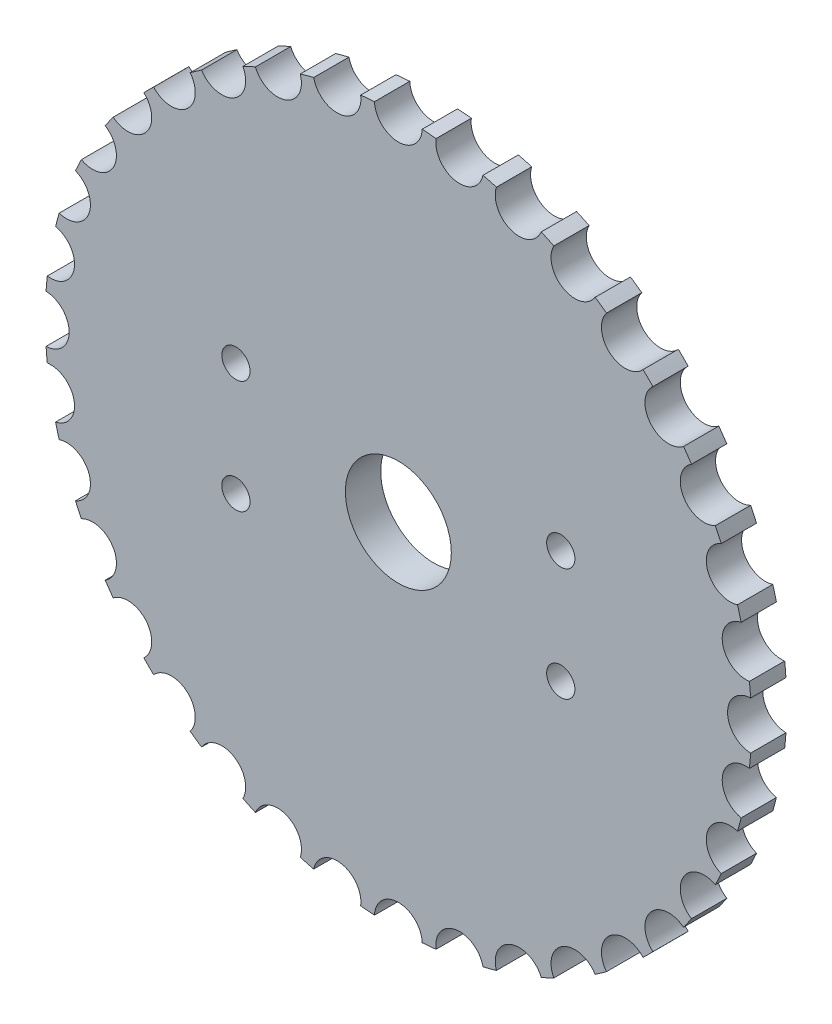
SolidWorks part; units mm, degrees
material "아크릴(내충격성)"
ref_plane "정면" through (0, 0, 0) normal (0, 0, 1) x (1, 0, 0)
ref_plane "윗면" through (0, 0, 0) normal (0, 1, 0) x (1, 0, 0)
ref_plane "우측면" through (0, 0, 0) normal (1, 0, 0) x (0, 0, -1)
sketch "스케치1" plane through (0, 0, 0) normal (0, 0, 1) x (1, 0, 0)
  circle A0 centre (0, 0) radius 50
  dimension "D1" = 100
extrude "보스-돌출1" add sketch "스케치1" along normal blind 5
sketch "스케치2" plane through (0, 0, 5) normal (0, 0, 1) x (1, 0, 0)
  line L0 (0, 0) -> (0, 53.4651) construction
  line L1 (0, 0) -> (9.1386, 52.0133) construction
  line L2 (0, 0) -> (-9.7027, 52.5525) construction
  circle A0 centre (4.373, 49.8084) radius 3.38
  circle A2 centre (0, 0) radius 50 construction
  circle A6 centre (11.6601, 43.4631) radius 3.38
  circle A7 centre (17.7347, 35.9488) radius 3.38
  circle A8 centre (22.4122, 27.4938) radius 3.38
  circle A9 centre (25.5503, 18.3551) radius 3.38
  circle A10 centre (27.0539, 8.8102) radius 3.38
  circle A11 centre (26.8772, -0.8507) radius 3.38
  circle A12 centre (25.0256, -10.3342) radius 3.38
  circle A13 centre (21.5553, -19.3521) radius 3.38
  circle A14 centre (16.5718, -27.6304) radius 3.38
  circle A15 centre (10.2265, -34.9175) radius 3.38
  circle A16 centre (2.7122, -40.9921) radius 3.38
  circle A17 centre (-5.7428, -45.6695) radius 3.38
  circle A18 centre (-14.8815, -48.8077) radius 3.38
  circle A19 centre (-24.4264, -50.3113) radius 3.38
  circle A20 centre (-34.0873, -50.1346) radius 3.38
  circle A21 centre (-43.5708, -48.283) radius 3.38
  circle A22 centre (-52.5887, -44.8127) radius 3.38
  circle A23 centre (-60.867, -39.8292) radius 3.38
  circle A24 centre (-68.1541, -33.4839) radius 3.38
  circle A25 centre (-74.2287, -25.9696) radius 3.38
  circle A26 centre (-78.9061, -17.5146) radius 3.38
  circle A27 centre (-82.0443, -8.3759) radius 3.38
  circle A28 centre (-83.5479, 1.169) radius 3.38
  circle A29 centre (-83.3712, 10.83) radius 3.38
  circle A30 centre (-81.5196, 20.3134) radius 3.38
  circle A31 centre (-78.0493, 29.3313) radius 3.38
  circle A32 centre (-73.0658, 37.6096) radius 3.38
  circle A33 centre (-66.7205, 44.8967) radius 3.38
  circle A34 centre (-59.2062, 50.9713) radius 3.38
  circle A35 centre (-50.7512, 55.6487) radius 3.38
  circle A36 centre (-41.6124, 58.7869) radius 3.38
  circle A37 centre (-32.0676, 60.2905) radius 3.38
  circle A38 centre (-22.4066, 60.1138) radius 3.38
  circle A39 centre (-12.9231, 58.2622) radius 3.38
  circle A40 centre (-3.9053, 54.7919) radius 3.38
  dimension "D1" = 106.9058
  dimension "D2" = 36
sketch "스케치4" plane through (0, 0, 5) normal (0, 0, 1) x (1, 0, 0)
  circle A0 centre (0, 0) radius 7.5
  dimension "D1" = 15
extrude "컷-돌출3" cut sketch "스케치4" against normal blind 10
sketch "스케치5" plane through (0, 0, 5) normal (0, 0, 1) x (1, 0, 0)
  line L0 (-52.1074, 0) -> (52.2141, 0) construction
  line L1 (-52.1074, -15) -> (52.2141, -15)
  line L2 (-52.1074, 15) -> (52.2141, 15)
  line L3 (0, 53.1222) -> (0, -55.2945) construction
  line L4 (-30, 53.1222) -> (-30, -55.2945)
  line L5 (30, 53.1222) -> (30, -55.2945)
  circle A0 centre (-23, 8) radius 2
  circle A1 centre (23, 8) radius 2
  circle A2 centre (23, -8) radius 2
  circle A3 centre (-23, -8) radius 2
  dimension "D5" = 4
  dimension "D7" = 7
  dimension "D6" = 7
  dimension "D1" = 15
  dimension "D2" = 15
  dimension "D3" = 30
  dimension "D4" = 30
extrude "컷-돌출4" cut sketch "스케치5" against normal blind 10 contours A3 | A0 | A1 | A2
sketch "스케치6" plane through (0, 0, 5) normal (0, 0, 1) x (1, 0, 0)
  circle A0 centre (0, 50) radius 3.38
  circle A1 centre (0, 0) radius 50 construction
  circle A2 centre (8.6824, 49.2404) radius 3.38
  circle A3 centre (17.101, 46.9846) radius 3.38
  circle A4 centre (25, 43.3013) radius 3.38
  circle A5 centre (32.1394, 38.3022) radius 3.38
  circle A6 centre (38.3022, 32.1394) radius 3.38
  circle A7 centre (43.3013, 25) radius 3.38
  circle A8 centre (46.9846, 17.101) radius 3.38
  circle A9 centre (49.2404, 8.6824) radius 3.38
  circle A10 centre (50, 0) radius 3.38
  circle A11 centre (49.2404, -8.6824) radius 3.38
  circle A12 centre (46.9846, -17.101) radius 3.38
  circle A13 centre (43.3013, -25) radius 3.38
  circle A14 centre (38.3022, -32.1394) radius 3.38
  circle A15 centre (32.1394, -38.3022) radius 3.38
  circle A16 centre (25, -43.3013) radius 3.38
  circle A17 centre (17.101, -46.9846) radius 3.38
  circle A18 centre (8.6824, -49.2404) radius 3.38
  circle A19 centre (0, -50) radius 3.38
  circle A20 centre (-8.6824, -49.2404) radius 3.38
  circle A21 centre (-17.101, -46.9846) radius 3.38
  circle A22 centre (-25, -43.3013) radius 3.38
  circle A23 centre (-32.1394, -38.3022) radius 3.38
  circle A24 centre (-38.3022, -32.1394) radius 3.38
  circle A25 centre (-43.3013, -25) radius 3.38
  circle A26 centre (-46.9846, -17.101) radius 3.38
  circle A27 centre (-49.2404, -8.6824) radius 3.38
  circle A28 centre (-50, 0) radius 3.38
  circle A29 centre (-49.2404, 8.6824) radius 3.38
  circle A30 centre (-46.9846, 17.101) radius 3.38
  circle A31 centre (-43.3013, 25) radius 3.38
  circle A32 centre (-38.3022, 32.1394) radius 3.38
  circle A33 centre (-32.1394, 38.3022) radius 3.38
  circle A34 centre (-25, 43.3013) radius 3.38
  circle A35 centre (-17.101, 46.9846) radius 3.38
  circle A36 centre (-8.6824, 49.2404) radius 3.38
  point P76 (0, 0)
  dimension "D1" = 36
extrude "컷-돌출5" cut sketch "스케치6" against normal through all
